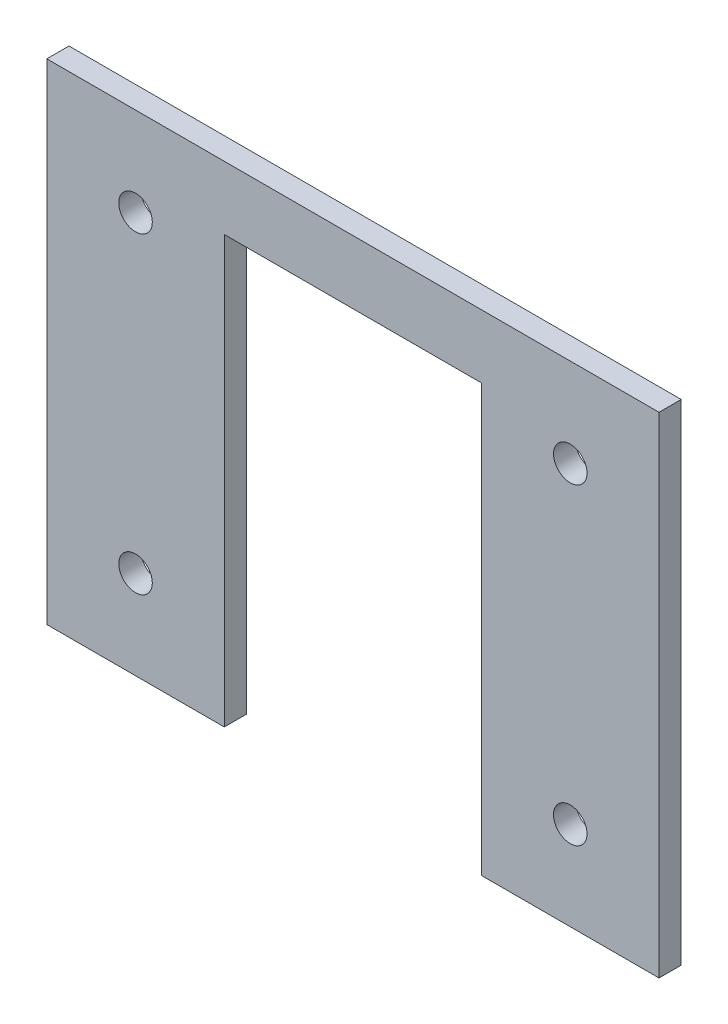
SolidWorks part; units mm, degrees
material "AISI 4130 Steel, annealed at 865C"
ref_plane "X-Y Datum" through (0, 0, 0) normal (0, 0, 1) x (1, 0, 0)
ref_plane "X-Z Datum" through (0, 0, 0) normal (0, 1, 0) x (1, 0, 0)
ref_plane "Y-Z Datum" through (0, 0, 0) normal (1, 0, 0) x (0, 0, -1)
sketch "Sketch1" plane through (0, 0, 0) normal (0, 0, 1) x (1, 0, 0)
  line L0 (11.5036, -3.7737) -> (36.9036, -3.7737)
  line L12 (11.5036, -3.7737) -> (11.5036, 66.3463)
  line L13 (11.5036, 66.3463) -> (36.9036, 66.3463)
  line L14 (36.9036, -3.7737) -> (36.9036, 57.2759)
  line L15 (99.1236, 66.3463) -> (73.7236, 66.3463)
  line L16 (73.7236, -3.7737) -> (73.7236, 57.2759)
  line L17 (99.1236, -3.7737) -> (73.7236, -3.7737)
  line L18 (99.1236, -3.7737) -> (99.1236, 66.3463)
  line L19 (36.9036, 66.3463) -> (73.7236, 66.3463)
  line L20 (36.9036, 57.2759) -> (73.7236, 57.2759)
  circle A4 centre (24.2036, 53.6463) radius 1.0911
  circle A5 centre (24.2036, 8.9263) radius 1.2652
  circle A6 centre (86.4236, 53.6463) radius 1.7171
  circle A7 centre (86.4236, 8.9263) radius 1.4554
extrude "Boss-Extrude1" add sketch "Sketch1" along normal blind 3.175
hole_wizard "M4 Clearance Hole1" positions "Sketch2" profile "Sketch3" hole size "M4" standard "ANSI Metric" end condition through all
sketch "Sketch2" plane through (0, 0, 3.175) normal (0, 0, 1) x (1, 0, 0)
  point P0 (24.2036, 53.6463)
  point P3 (24.2036, 8.9263)
  point P6 (86.4236, 8.9263)
  point P9 (86.4236, 53.6463)
sketch "Sketch3" plane through (24.2036, 53.6463, 3.175) normal (1, 0, 0) x (0, -1, 0)
  line L0 (0, 0) -> (0, 3.175)
  line L1 (0, 3.175) -> (2.4, 3.175)
  line L2 (2.4, 3.175) -> (2.4, 0)
  line L5 (2.4, 0) -> (0, 0)
  line L11 (0, -6.35) -> (0, 107.95) construction
  dimension "Thru Hole Dia." = 4.8
  dimension "Thru Hole Depth" = 3.175
